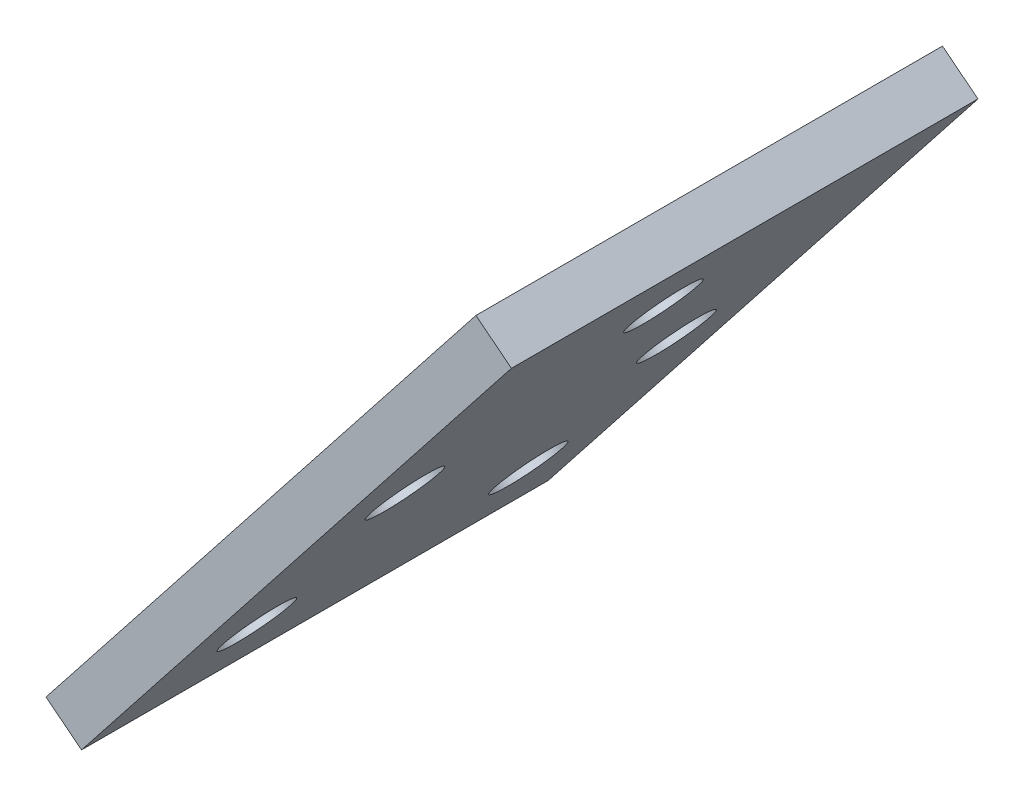
SolidWorks part; units mm, degrees
ref_plane "Ground Plane" through (0, 0, 0) normal (0, 0, 1) x (1, 0, 0)
ref_plane "Side Plane" through (0, 0, 0) normal (0, 1, 0) x (1, 0, 0)
ref_plane "Rear Axle Centerline" through (0, 0, 0) normal (1, 0, 0) x (0, 0, -1)
sketch "Chassis Side View" plane through (0, 0, 0) normal (0, 1, 0) x (1, 0, 0)
  line L0 (0, -381) -> (2300, -381) construction
  line L1 (1150, -381) -> (1150, -856.742)
  line L2 (2150, -381) -> (2150, -1062.9307) construction
  line L3 (-753.0356, 0) -> (753.0356, 0) construction
  line L4 (2450, -381) -> (2450, -1062.9307) construction
  dimension "D1" = 2300
  dimension "D2" = 475.742
  dimension "D3" = 1150
  dimension "D4" = 381
  dimension "D5" = 150
  dimension "D6" = 150
ref_plane "Front Axle Centerline" through (2300, 0, 0) normal (1, 0, 0) x (0, 0, -1)
sketch "Front Wheel Assy Constraints" plane through (2300, 0, 0) normal (1, 0, 0) x (0, 0, -1)
  line L0 (0, 727.5) -> (0, 822.5)
  line L1 (0, 822.5) -> (-271.78, 822.5)
  line L2 (-271.78, 822.5) -> (-551.18, 822.5)
  line L3 (-551.18, 822.5) -> (-551.18, 727.5)
  line L4 (-551.18, 775) -> (0, 775) construction
  line L5 (-271.78, 822.5) -> (-271.78, 775) construction
  line L6 (-551.18, 727.5) -> (-445.4516, 727.5)
  line L7 (-445.4516, 727.5) -> (-445.4516, 798.5)
  line L8 (-445.4516, 798.5) -> (-105.7284, 798.5)
  line L9 (-105.7284, 798.5) -> (-105.7284, 727.5)
  line L10 (-105.7284, 727.5) -> (0, 727.5)
  line L11 (0, 0) -> (-673.9047, 0) construction
  line L13 (0, 753.0356) -> (0, -753.0356) construction
  dimension "D1" = 95
  dimension "D2" = 279.4
  dimension "D3" = 271.78
  dimension "D4" = 23.5
  dimension "D5" = 1550
sketch "Front Sus Front View" plane through (2300, 0, 0) normal (1, 0, 0) x (0, 0, -1)
  line L0 (0, 775) -> (0, 768.65) construction
  line L1 (0, 753.0356) -> (0, -753.0356) construction
  line L2 (0, 768.65) -> (-762, 634.2888) construction
  line L3 (0, 768.65) -> (-745.3671, 768.65) construction
  line L4 (-366.7919, -1090.2477) -> (-525.9451, 520.8571) construction
  line L5 (-366.7919, -1090.2477) -> (-379.5678, 520.8571) construction
  line L6 (-366.7919, -1090.2477) -> (0, 775) construction
  line L7 (-525.9451, 520.8571) -> (-541, 673.2571)
  line L8 (-379.5678, 520.8571) -> (-381, 701.4694)
  line L9 (0, 0) -> (-152.4, 0) construction
  line L13 (-525.9451, 520.8571) -> (-379.5678, 520.8571) construction
  dimension "D1" = 6.35
  dimension "D2" = 10
  dimension "D3" = 152.4
  dimension "D4" = 1865.2477
  dimension "D6" = 381
  dimension "D7" = 541
  dimension "D8" = 153.1418
  dimension "D5" = 152.4
ref_plane "Fron Wheel Side View Plane" through (0, 775, 0) normal (0, 1, 0) x (1, 0, 0)
sketch "Front SVSA" plane through (0, 775, 0) normal (0, 1, 0) x (1, 0, 0)
  line L0 (2271.684, -676.7175) -> (2328.316, 133.1575)
  line L1 (2300, 0) -> (2300, -771.0839) construction
  line L2 (2300, 0) -> (-2450.054, -116.0888) construction
  line L3 (-2450.054, -116.0888) -> (2298.2335, -297.0415) construction
  line L4 (-753.0356, 0) -> (753.0356, 0) construction
  point P5 (2300, -271.78)
  dimension "D1" = 4
  dimension "D2" = 1.4
  dimension "D3" = 4750.054
sketch3d "Front Chassis Side Axes"
  line L0 (2300, 520.8571, 379.5678) -> (2300, 701.4694, 381) construction
  line L1 (2300, 520.8571, 525.9451) -> (2300, 673.2571, 541) construction
  line L2 (2300, 520.8571, 379.5678) -> (2300, 701.4694, 381) construction
  line L3 (2300, 520.8571, 525.9451) -> (2300, 673.2571, 541) construction
  line L4 (2300, 673.2571, 541) -> (2300, 775, 551.0507) construction
  line L5 (2300, 701.4694, 381) -> (2300, 775, 381.5831) construction
  line L6 (2300, 775, 0) -> (2300, 775, 771.0839) construction
  line L7 (-2450.054, 775, 116.0888) -> (2349.7917, 775, 555.6101) construction
  line L8 (-2450.054, 775, 116.0888) -> (2349.9221, 775, 384.3734) construction
  line L9 (2349.9221, 775, 384.3734) -> (2177.377, 520.8571, 372.714) construction
  line L10 (2349.7917, 775, 555.6101) -> (2225.4174, 520.8571, 519.1156) construction
  line L11 (2300, 520.8571, 525.9451) -> (2300, 520.8571, 519.1156) construction
  line L12 (2300, 520.8571, 519.1156) -> (2225.4174, 520.8571, 519.1156) construction
  line L13 (2598.7501, 520.8571, 553.3017) -> (1702.4998, 520.8571, 471.2321)
  line L14 (2300, 520.8571, 379.5678) -> (2300, 520.8571, 372.714) construction
  line L15 (2300, 520.8571, 372.714) -> (2177.377, 520.8571, 372.714) construction
  line L16 (2599.5325, 520.8571, 396.3095) -> (1700.935, 520.8571, 346.0843)
  dimension "D1" = 50
  dimension "D2" = 50
  dimension "D3" = 600
  dimension "D4" = 300
  dimension "D5" = 600
  dimension "D6" = 300
sketch3d "Front Left Control Arm"
  line L0 (2300, 520.8571, 379.5678) -> (2300, 701.4694, 381) construction
  line L2 (2300, 520.8571, 379.5678) -> (2300, 701.4694, 381) construction
  line L3 (2300, 520.8571, 525.9451) -> (2300, 673.2571, 541) construction
  line L4 (2598.7501, 520.8571, 553.3017) -> (1702.4998, 520.8571, 471.2321) construction
  line L5 (2599.5325, 520.8571, 396.3095) -> (1700.935, 520.8571, 346.0843) construction
  line L6 (2598.7501, 520.8571, 553.3017) -> (1702.4998, 520.8571, 471.2321) construction
  line L7 (2599.5325, 520.8571, 396.3095) -> (1700.935, 520.8571, 346.0843) construction
  line L8 (2450, 520.8571, 539.6806) -> (2280.5957, 673.2571, 539.2232)
  line L9 (2280.5957, 673.2571, 539.2232) -> (2150, 520.8571, 512.2097)
  line L10 (2300, 520.8571, 525.9451) -> (2300, 673.2571, 541) construction
  line L11 (2300, 673.2571, 541) -> (2280.5957, 673.2571, 539.2232) construction
  line L12 (2271.684, 775, 676.7175) -> (2328.316, 775, -133.1575) construction
  line L13 (2150, 0, 512.2097) -> (2150, 520.8571, 512.2097) construction
  line L14 (2292.3517, 701.4694, 380.5725) -> (2292.3517, 775, 381.1556) construction
  line L15 (2150, 0, 381) -> (2150, 0, 1062.9307) construction
  line L16 (2450, 0, 539.6806) -> (2450, 520.8571, 539.6806) construction
  line L17 (2450, 0, 381) -> (2450, 0, 1062.9307) construction
  line L18 (2450, 520.8571, 387.9517) -> (2292.3517, 701.4694, 380.5725)
  line L19 (2292.3517, 701.4694, 380.5725) -> (2150, 520.8571, 371.1838)
  line L20 (2300, 701.4694, 381) -> (2292.3517, 701.4694, 380.5725) construction
  line L21 (2450, 0, 387.9517) -> (2450, 520.8571, 387.9517) construction
  line L22 (2150, 0, 371.1838) -> (2150, 520.8571, 371.1838) construction
  line L23 (2280.5957, 673.2571, 539.2232) -> (2280.5957, 775, 549.2738) construction
sketch3d "Front Control Arm"
  line L0 (2450, 520.8571, 387.9517) -> (2292.3517, 701.4694, 380.5725) construction
  line L1 (2292.3517, 701.4694, 380.5725) -> (2150, 520.8571, 371.1838) construction
  line L2 (2280.5957, 673.2571, 539.2232) -> (2150, 520.8571, 512.2097) construction
  line L3 (2450, 520.8571, 539.6806) -> (2280.5957, 673.2571, 539.2232) construction
  line L4 (2450, 520.8571, 387.9517) -> (2292.3517, 701.4694, 380.5725)
  line L5 (2292.3517, 701.4694, 380.5725) -> (2150, 520.8571, 371.1838)
  line L6 (2280.5957, 673.2571, 539.2232) -> (2150, 520.8571, 512.2097)
  line L7 (2450, 520.8571, 539.6806) -> (2280.5957, 673.2571, 539.2232)
  line L8 (2450, -520.8571, 539.6806) -> (2280.5957, -673.2571, 539.2232)
  line L9 (2280.5957, -673.2571, 539.2232) -> (2150, -520.8571, 512.2097)
  line L10 (2292.3517, -701.4694, 380.5725) -> (2150, -520.8571, 371.1838)
  line L11 (2450, -520.8571, 387.9517) -> (2292.3517, -701.4694, 380.5725)
ref_plane "Max Droop Plane" through (0, 0, -25.4) normal (0, 0, 1) x (1, 0, 0)
sketch3d "Shock"
  line L0 (2292.3517, 701.4694, 380.5725) -> (2293.5626, 664.4705, 414.2387) construction
  line L1 (2300, 520.8571, 525.9451) -> (2298.2629, 520.8571, 544.9158) construction
  line L2 (2150, 520.8571, 512.2097) -> (2450, 520.8571, 539.6806) construction
  line L3 (2300, 520.8571, 525.9451) -> (2300, 230.5152, 525.9451) construction
  line L4 (2293.5626, 664.4705, 414.2387) -> (2298.2629, 520.8571, 544.9158)
  dimension "D1" = 50.038
  dimension "D2" = 19.05
sketch3d "Parametric Analysis"
  line L2 (2300, 822.5, 0) -> (2300, 822.5, 271.78) construction
  line L3 (2300.4137, 822.5, 271.7939) -> (2300.4137, 822.5, -88.8537) construction
  line L4 (2450, 520.8571, 387.9517) -> (2292.3526, 701.4695, 380.5568)
  line L5 (2292.3526, 701.4695, 380.5568) -> (2150, 520.8571, 371.1838)
  line L6 (2450, 520.8571, 539.6806) -> (2280.5972, 673.2586, 539.2077)
  line L7 (2280.5972, 673.2586, 539.2077) -> (2150, 520.8571, 512.2097)
  line L8 (2292.3517, 701.4694, 380.5725) -> (2300, 822.5, 271.78) construction
  line L9 (2450, 520.8571, 387.9517) -> (2292.3517, 701.4694, 380.5725) construction
  line L10 (2292.3517, 701.4694, 380.5725) -> (2150, 520.8571, 371.1838) construction
  line L11 (2450, 520.8571, 539.6806) -> (2280.5957, 673.2571, 539.2232) construction
  line L12 (2280.5957, 673.2571, 539.2232) -> (2150, 520.8571, 512.2097) construction
  line L13 (2280.5957, 673.2571, 539.2232) -> (2292.3517, 701.4694, 380.5725) construction
  line L14 (2300, 822.5, 271.78) -> (2280.5957, 673.2571, 539.2232) construction
  line L15 (2300, 822.5, 271.78) -> (2300.4132, 720.8156, 271.78) construction
  line L16 (2280.5972, 673.2586, 539.2077) -> (2300.4137, 822.5, 271.7939) construction
  line L17 (2300.4137, 822.5, 271.7939) -> (2292.3526, 701.4695, 380.5568) construction
  line L18 (2280.5972, 673.2586, 539.2077) -> (2292.3526, 701.4695, 380.5568) construction
  line L19 (2300.4137, 822.5, 271.7939) -> (2300.4137, 720.8148, 271.7641) construction
  line L23 (2292.3517, 701.4694, 380.5725) -> (2265.8007, 667.7821, 378.8214) construction
  line L30 (2265.8007, 667.7821, 378.8214) -> (2325.2406, 663.7898, 382.112) construction
  line L31 (2325.2406, 663.7898, 382.112) -> (2293.5626, 664.4705, 414.2387) construction
  line L32 (2292.3517, 701.4694, 380.5725) -> (2325.2406, 663.7898, 382.112) construction
  line L33 (2293.5626, 664.4705, 414.2387) -> (2265.8007, 667.7821, 378.8214) construction
  line L34 (2292.3526, 701.4695, 380.5568) -> (2293.5633, 664.4722, 414.2247) construction
  line L35 (2292.3517, 701.4694, 380.5725) -> (2293.5626, 664.4705, 414.2387) construction
  line L39 (2300.4137, 822.5, 271.7939) -> (2300.4137, 822.5798, 0.014)
  line L40 (2300.4137, 822.5798, 0.014) -> (2300.4137, 727.5798, -0.014)
  line L41 (2300, 727.5, 0) -> (2300, 822.5, 0) construction
  line L42 (2298.2629, 520.8571, 544.9158) -> (2293.5633, 664.4722, 414.2247)
  point P5 (2300.4137, 775.0798, 0)
  dimension "D1" = 25.4
  dimension "D2" = 194.2357
  dimension "D3" = 0.0798
  dimension "D4" = 0.017
sketch3d "3DSketch1"
  line L0 (2293.5626, 664.4705, 414.2387) -> (2298.2629, 520.8571, 544.9158) construction
  line L1 (2280.5972, 673.2586, 539.2077) -> (2150, 520.8571, 512.2097) construction
  line L2 (2450, 520.8571, 539.6806) -> (2280.5972, 673.2586, 539.2077) construction
  line L3 (2292.3526, 701.4695, 380.5568) -> (2150, 520.8571, 371.1838) construction
  line L4 (2450, 520.8571, 387.9517) -> (2292.3526, 701.4695, 380.5568) construction
  line L5 (2293.5626, 664.4705, 414.2387) -> (2298.2629, 520.8571, 544.9158)
  line L6 (2280.5972, 673.2586, 539.2077) -> (2150, 520.8571, 512.2097)
  line L7 (2450, 520.8571, 539.6806) -> (2280.5972, 673.2586, 539.2077)
  line L8 (2292.3526, 701.4695, 380.5568) -> (2150, 520.8571, 371.1838)
  line L9 (2450, 520.8571, 387.9517) -> (2292.3526, 701.4695, 380.5568)
  line L10 (2450, 520.8571, 539.6806) -> (2450, 470.0571, 539.6806) construction
  line L11 (2150, 520.8571, 512.2097) -> (2150, 470.0571, 512.2097) construction
  line L12 (2298.2629, 520.8571, 544.9158) -> (2298.2629, 470.0571, 544.9158) construction
  line L13 (2450, 520.8571, 387.9517) -> (2450, 470.0571, 387.9517) construction
  line L14 (2150, 520.8571, 371.1838) -> (2150, 470.0571, 371.1838) construction
  line L15 (2150, -520.8571, 512.2097) -> (2150, -470.0571, 512.2097) construction
  line L16 (2298.2629, -520.8571, 544.9158) -> (2298.2629, -470.0571, 544.9158) construction
  line L17 (2450, -520.8571, 539.6806) -> (2450, -470.0571, 539.6806) construction
  line L18 (2293.5626, -664.4705, 414.2387) -> (2298.2629, -520.8571, 544.9158)
  line L19 (2280.5972, -673.2586, 539.2077) -> (2150, -520.8571, 512.2097)
  line L20 (2450, -520.8571, 539.6806) -> (2280.5972, -673.2586, 539.2077)
  line L21 (2450, -520.8571, 387.9517) -> (2450, -470.0571, 387.9517) construction
  line L22 (2150, -520.8571, 371.1838) -> (2150, -470.0571, 371.1838) construction
  line L23 (2292.3526, -701.4695, 380.5568) -> (2150, -520.8571, 371.1838)
  line L24 (2450, -520.8571, 387.9517) -> (2292.3526, -701.4695, 380.5568)
  line L27 (2300, 775, 551.18) -> (2300, 775, 0) construction
  dimension "D1" = 50.8
  dimension "D2" = 304.9478
  dimension "D3" = 544.9185
ref_plane "Plane1" through (0, 718.612, 0) normal (0, 1, 0) x (1, 0, 0)
ref_plane "Plane2" through (0, 0, 512.2097) normal (0, 0, 1) x (1, 0, 0)
ref_plane "Plane4" through (2150, 520.8571, 371.1838) normal (0, 0, 1) x (1, 0, 0)
sketch "Sketch3" plane through (2150, 520.8571, 371.1838) normal (0, 0, 1) x (1, 0, 0)
  line L0 (0, 0) -> (-25.9867, 20.4819) construction
  line L1 (142.3526, 180.6124) -> (0, 0) construction
sketch "Sketch1" plane through (0, 0, 512.2097) normal (0, 0, 1) x (1, 0, 0)
  line L0 (2150, 520.8571) -> (2116.4573, 549.6008) construction
  line L1 (2280.5972, 673.2586) -> (2150, 520.8571) construction
  point P5 (2141.6294, 528.0301)
  dimension "D1" = 11.0236
ref_plane "Plane3" through (2141.6294, 528.0301, 512.2097) normal (-0.7854, 0.619, 0) x (0, 0, 1)
sketch "Sketch2" plane through (2141.6294, 528.0301, 512.2097) normal (-0.7854, 0.619, 0) x (0, 0, 1)
  line L1 (-32.7323, 17.9747) -> (32.7323, 17.9747)
  line L2 (-32.7323, 17.9747) -> (-32.7323, -79.4749)
  line L3 (-32.7323, -79.4749) -> (32.7323, -79.4749)
  line L4 (32.7323, 17.9747) -> (32.7323, -79.4749)
  circle A0 centre (0, -0.4521) radius 4.7625
  circle A1 centre (-19.05, -28.2642) radius 4.7625
  circle A2 centre (19.05, -28.2642) radius 4.7625
  circle A3 centre (19.05, -61.8488) radius 4.7625
  circle A4 centre (-19.05, -61.8488) radius 4.7625
  point P15 (0, 17.9747)
  dimension "D1" = 9.525
  dimension "D2" = 9.525
  dimension "D3" = 9.525
  dimension "D4" = 9.525
  dimension "D5" = 9.525
  dimension "D6" = 19.05
  dimension "D7" = 19.05
extrude "Boss-Extrude1" add sketch "Sketch2" along normal blind 6.35
equation "\"wheelbase\"= 2.3m"
equation "\"track_front_outer\"= 1.55m"
equation "\"cg_h\"= 18.73in"
equation "\"cg_b\"= \"wheelbase\" / 2"
equation "\"chassis_ride_height\"= 15in"
equation "\"hub_offset\"= 23.5mm"
equation "\"tire_radius\"= 11in"
equation "\"tire_radius_loaded\"= 10.7in"
equation "\"tire_width\"= 95mm"
equation "\"static_camber\"= 0deg"
equation "\"caster_static\"= 4deg"
equation "\"control_arm_ratio\"= 0.95"
equation "\"roll_center_height\"= 6in"
equation "\"scrub_radius\"= 0.25in"
equation "\"camber_change_rate\"= 0.5deg'per inch of travel"
equation "\"fvsa_length\"= atn ( 1 / \"camber_change_rate\" )"
equation "\"svsa_length\"= 2.5 * \"wheelbase\""
equation "\"svsa_height\"= 1"
equation "\"anti_squat_rear\"= 0.15"
equation "\"front_brakes\"= .75"
equation "\"anti_dive_front\"= 0.1"
equation "\"D1@Chassis Side View\" = \"wheelbase\""
equation "\"D2@Chassis Side View\" = \"cg_h\""
equation "\"D3@Chassis Side View\" = \"cg_b\""
equation "\"D4@Chassis Side View\" = \"chassis_ride_height\""
equation "\"D1@Front Axle Centerline\"=\"wheelbase\""
equation "\"D1@Front Wheel Assy Constraints\" = \"tire_width\""
equation "\"D2@Front Wheel Assy Constraints\" = \"tire_radius\""
equation "\"D3@Front Wheel Assy Constraints\" = \"tire_radius_loaded\""
equation "\"D4@Front Wheel Assy Constraints\" = \"hub_offset\""
equation "\"D1@Front Sus Front View\" = \"scrub_radius\""
equation "\"static_kingpin\"= 10deg"
equation "\"D2@Front Sus Front View\" = \"static_kingpin\""
equation "\"D3@Front Sus Front View\" = \"roll_center_height\""
equation "\"D6@Front Sus Front View\" = \"chassis_ride_height\""
equation "\"D7@Front Sus Front View\"=\"chassis_ride_height\" + 160mm"
equation "\"D1@Front SVSA\" = \"caster_static\""
equation "\"D4@Front Sus Front View\"=\"fvsa_length\"+10"
equation "\"D5@Front Wheel Assy Constraints\"=\"track_front_outer\""
equation "\"phi_front\"= atn ( \"anti_dive_front\" / \"front_brakes\" * \"cg_h\" / \"wheelbase\" )"
equation "\"anti_lift_rear\"= 0.1"
equation "\"a\"= 0"
